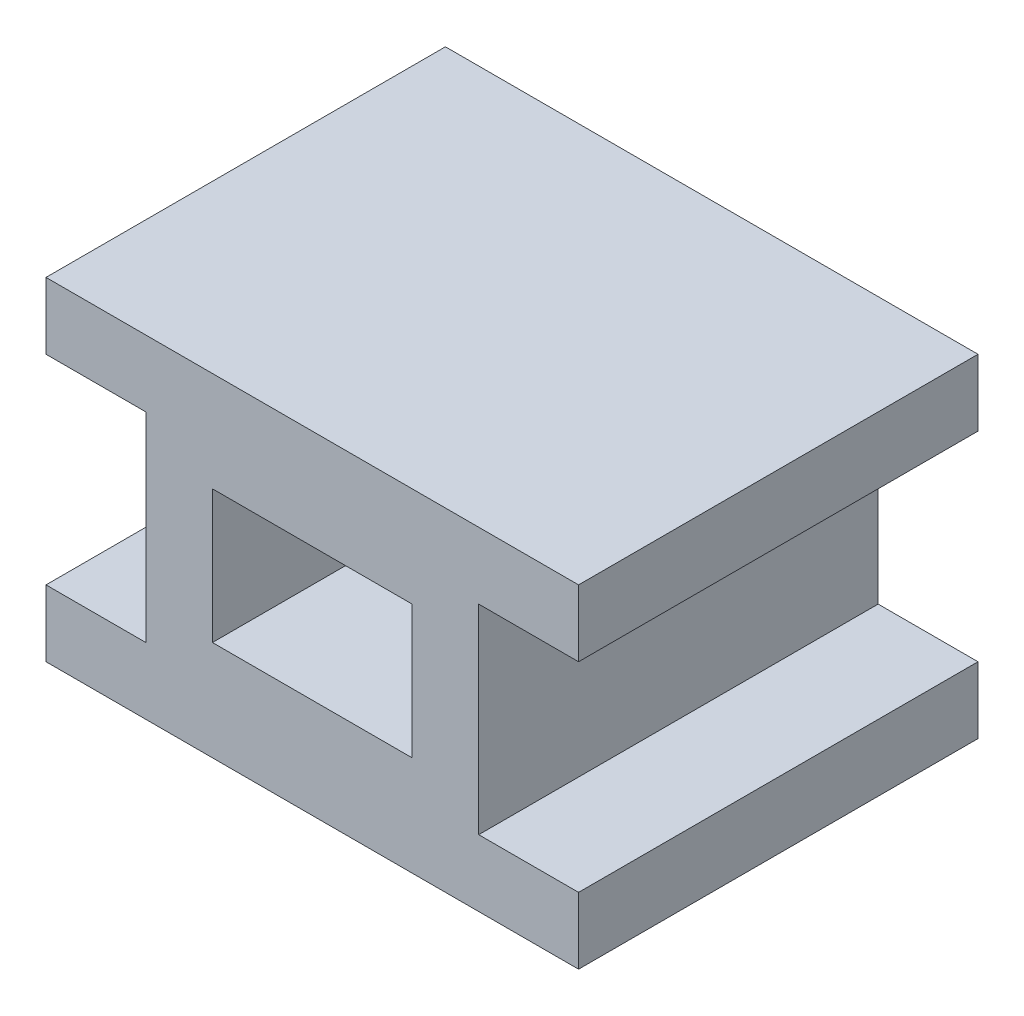
SolidWorks part; units mm, degrees
ref_plane "Front Plane" through (0, 0, 0) normal (0, 0, 1) x (1, 0, 0)
ref_plane "Top Plane" through (0, 0, 0) normal (0, 1, 0) x (1, 0, 0)
ref_plane "Right Plane" through (0, 0, 0) normal (1, 0, 0) x (0, 0, -1)
sketch "Sketch1" plane through (0, 0, 0) normal (0, 0, 1) x (1, 0, 0)
  line L0 (-6.7705, 20.623) -> (-6.7705, -36.6885) construction
  line L1 (33.2295, -36.4426) -> (-46.7705, -36.4426)
  line L2 (-46.7705, -36.4426) -> (-46.7705, -26.4426)
  line L3 (-46.7705, -26.4426) -> (-31.7705, -26.4426)
  line L4 (-31.7705, -26.4426) -> (-31.7705, 3.5574)
  line L5 (-31.7705, 3.5574) -> (-46.7705, 3.5574)
  line L6 (-46.7705, 3.5574) -> (-46.7705, 13.5574)
  line L7 (-46.7705, 13.5574) -> (33.2295, 13.5574)
  line L8 (33.2295, 3.5574) -> (33.2295, 13.5574)
  line L9 (-21.7705, -1.4426) -> (8.2295, -1.4426)
  line L10 (-21.7705, -1.4426) -> (-21.7705, -21.4426)
  line L11 (-21.7705, -21.4426) -> (8.2295, -21.4426)
  line L13 (18.2295, 3.5574) -> (33.2295, 3.5574)
  line L14 (8.2295, -1.4426) -> (8.2295, -21.4426)
  line L15 (18.2295, -26.4426) -> (18.2295, 3.5574)
  line L16 (33.2295, -26.4426) -> (18.2295, -26.4426)
  line L17 (33.2295, -36.4426) -> (33.2295, -26.4426)
  point P4 (-6.7705, -1.4426)
  point P10 (-6.7705, -11.4426)
  point P15 (-6.7705, -21.4426)
  point P20 (-6.7705, 13.5574)
  point P23 (-6.7705, -36.4426)
  dimension "D1" = 40
  dimension "D2" = 10
  dimension "D3" = 15
  dimension "D4" = 15
  dimension "D5" = 10
  dimension "D6" = 30
  dimension "D9" = 5
  dimension "D10" = 10
extrude "Boss-Extrude1" add sketch "Sketch1" along normal mid plane 60
